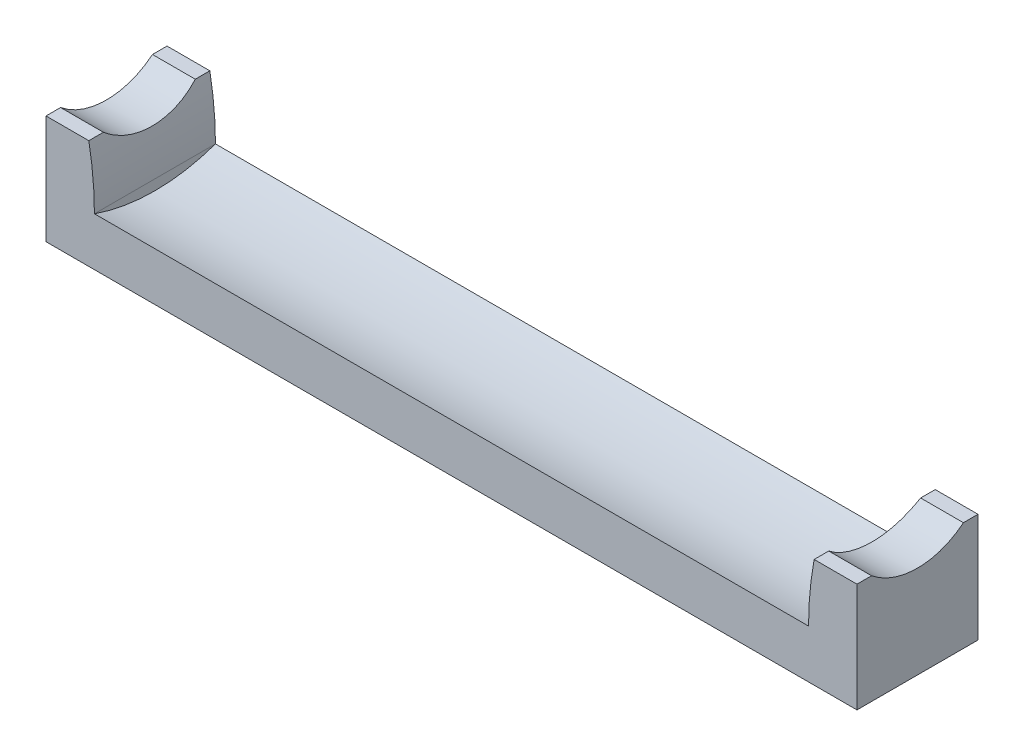
SolidWorks part; units mm, degrees
ref_plane "Plano frontal" through (0, 0, 0) normal (0, 0, 1) x (1, 0, 0)
ref_plane "Plano superior" through (0, 0, 0) normal (0, 1, 0) x (1, 0, 0)
ref_plane "Plano direito" through (0, 0, 0) normal (1, 0, 0) x (0, 0, -1)
sketch "Esboço1" plane through (0, 0, 0) normal (0, 0, 1) x (1, 0, 0)
  line L0 (0, 0) -> (0, 18)
  line L1 (0, 18) -> (8, 18)
  line L2 (8, 18) -> (8, 8)
  line L3 (8, 8) -> (126, 8)
  line L4 (126, 8) -> (126, 18)
  line L5 (126, 18) -> (134, 18)
  line L6 (134, 18) -> (134, 0)
  line L7 (134, 0) -> (0, 0)
  dimension "D1" = 118
  dimension "D2" = 8
  dimension "D3" = 8
  dimension "D4" = 10
  dimension "D5" = 8
extrude "Ressalto-extrusão1" add sketch "Esboço1" along normal blind 20
sketch "Esboço2" plane through (8, 0, 0) normal (1, 0, 0) x (0, 0, -1)
  line L1 (-20, 8) -> (0, 8) construction
  line L2 (-20, 8) -> (0, 8)
  arc A0 (-20, 8) -> (0, 8) centre (-10, 36.2843) ccw
  dimension "D1" = 30
extrude "Corte-extrusão1" cut sketch "Esboço2" along normal up to surface (118 mm away) up to face at (126, 13, 10)
sketch "Esboço3" plane through (0, 0, 0) normal (0, 0, -1) x (-1, 0, 0)
  line L0 (-8, 8) -> (-8, 18) construction
  line L1 (-8, 18) -> (0, 18) construction
  line L2 (-8, 18) -> (-7.0738, 18)
  line L3 (-8, 8) -> (-8, 18)
  line L4 (-67, 0) -> (-67, 46.1106) construction
  line L5 (0, 0) -> (-134, 0) construction
  line L6 (-126, 8) -> (-126, 18)
  line L7 (-126, 18) -> (-126.9262, 18)
  arc A0 (-8, 8) -> (-7.0738, 18) centre (46.4493, 8) cw
  arc A1 (-126, 8) -> (-126.9262, 18) centre (-180.4493, 8) ccw
  point P14 (-7.0738, 18)
extrude "Corte-extrusão2" cut sketch "Esboço3" against normal through all
sketch "Esboço4" plane through (0, 0, 0) normal (-1, 0, 0) x (0, 0, 1)
  line L0 (10, 0) -> (10, 27.2538) construction
  line L1 (20, 0) -> (0, 0) construction
  circle A0 centre (10, 27.2538) radius 11.9694
  point P3 (10, 23.4638)
  point P6 (10, 27.2538)
extrude "Corte-extrusão3" cut sketch "Esboço4" against normal through all
